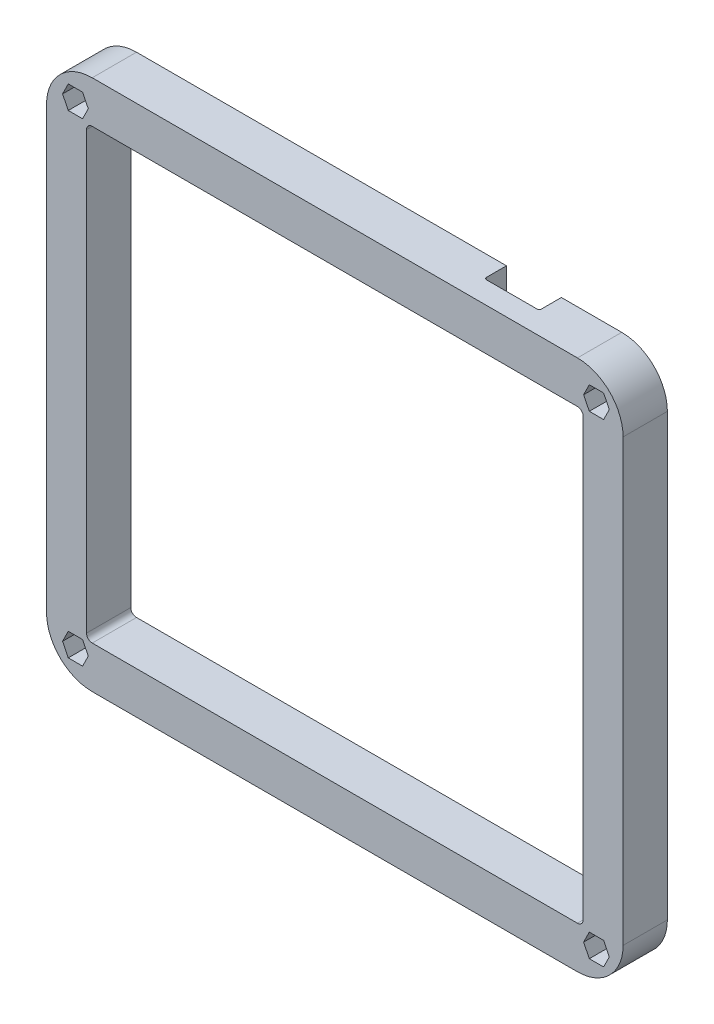
SolidWorks part; units mm, degrees
ref_plane "Ebene vorne" through (0, 0, 0) normal (0, 0, 1) x (1, 0, 0)
ref_plane "Ebene oben" through (0, 0, 0) normal (0, 1, 0) x (1, 0, 0)
ref_plane "Ebene rechts" through (0, 0, 0) normal (1, 0, 0) x (0, 0, -1)
sketch "Skizze1" plane through (0, 0, 0) normal (0, 0, 1) x (1, 0, 0)
  line L0 (-169.0581, -51.0905) -> (-85.55, -51.0905) construction
  line L1 (-169.0581, -41.5905) -> (-85.55, -41.5905) construction
  line L2 (-59.5275, -41.5905) -> (-73.15, -41.5905) construction
  line L3 (-59.5275, -51.0905) -> (-73.15, -51.0905) construction
  line L4 (-179.3474, -150.8036) -> (-179.3474, -52.3842) construction
  line L10 (-73.15, -41.5905) -> (-85.55, -41.5905)
  line L11 (-170.3518, -150.803) -> (-170.3518, -52.3842) construction
  line L12 (-58.2338, -52.3842) -> (-58.2338, -150.803) construction
  line L14 (-59.5275, -161.5967) -> (-169.0581, -161.5967) construction
  line L15 (-59.5275, -152.0967) -> (-169.0581, -152.0967) construction
  line L21 (-73.15, -51.0905) -> (-85.55, -51.0905)
  line L22 (-176.1768, -155.0967) -> (-167.1691, -155.0967) construction
  line L23 (-172.8474, -149.9491) -> (-172.8474, -160.7097) construction
  line L30 (-56.8493, -152.4967) -> (-53.6183, -152.4967)
  line L31 (-53.6183, -152.4967) -> (-52.3338, -155.0967)
  line L32 (-52.3338, -155.0967) -> (-53.6183, -157.6967)
  line L33 (-53.6183, -157.6967) -> (-56.8493, -157.6967)
  line L34 (-56.8493, -157.6967) -> (-58.1338, -155.0967)
  line L35 (-58.1338, -155.0967) -> (-56.8493, -152.4967)
  line L36 (-55.2338, -149.418) -> (-55.2338, -157.4313) construction
  line L37 (-53.5053, -155.0967) -> (-60.8819, -155.0967) construction
  line L38 (-55.2338, -45.3904) -> (-55.2338, -52.2981) construction
  line L39 (-59.8357, -48.0905) -> (-52.3338, -48.0905) construction
  line L40 (-56.8493, -45.4905) -> (-53.6183, -45.4905)
  line L41 (-53.6183, -45.4905) -> (-52.3338, -48.0905)
  line L42 (-52.3338, -48.0905) -> (-53.6183, -50.6905)
  line L43 (-53.6183, -50.6905) -> (-56.8493, -50.6905)
  line L44 (-56.8493, -50.6905) -> (-58.1338, -48.0905)
  line L45 (-58.1338, -48.0905) -> (-56.8493, -45.4905)
  line L46 (-172.8474, -46.2241) -> (-172.8474, -53.8481) construction
  line L47 (-169.0581, -51.0905) -> (-85.55, -51.0905)
  line L48 (-174.4629, -45.4905) -> (-171.2319, -45.4905)
  line L49 (-171.2319, -45.4905) -> (-169.9474, -48.0905)
  line L50 (-169.9474, -48.0905) -> (-171.2319, -50.6905)
  line L51 (-171.2319, -50.6905) -> (-174.4629, -50.6905)
  line L52 (-174.4629, -50.6905) -> (-175.7474, -48.0905)
  line L53 (-175.7474, -48.0905) -> (-174.4629, -45.4905)
  line L60 (-171.2319, -152.4967) -> (-174.4629, -152.4967)
  line L61 (-174.4629, -152.4967) -> (-175.7474, -155.0967)
  line L62 (-175.7474, -155.0967) -> (-174.4629, -157.6967)
  line L63 (-174.4629, -157.6967) -> (-171.2319, -157.6967)
  line L64 (-171.2319, -157.6967) -> (-169.9474, -155.0967)
  line L65 (-169.9474, -155.0967) -> (-171.2319, -152.4967)
  line L66 (-167.3158, -48.0905) -> (-176.3704, -48.0905) construction
  line L67 (-49.2275, -51.8905) -> (-49.2275, -151.2967) construction
  line L68 (-49.2275, -51.8905) -> (-49.2275, -151.2967)
  line L83 (-169.0581, -41.5905) -> (-85.55, -41.5905)
  line L84 (-59.5275, -41.5905) -> (-73.15, -41.5905)
  line L85 (-59.5275, -51.0905) -> (-73.15, -51.0905)
  line L86 (-179.3474, -150.8036) -> (-179.3474, -52.3842)
  line L87 (-170.3518, -150.803) -> (-170.3518, -52.3842)
  line L88 (-58.2338, -52.3842) -> (-58.2338, -150.803)
  line L90 (-59.5275, -161.5967) -> (-169.0581, -161.5967)
  line L91 (-59.5275, -152.0967) -> (-169.0581, -152.0967)
  arc A0 (-169.0581, -51.0905) -> (-170.3518, -52.3842) centre (-169.0581, -52.3842) ccw construction
  arc A1 (-169.0581, -41.5905) -> (-179.3474, -52.3842) centre (-169.0581, -51.8916) ccw construction
  arc A2 (-58.2338, -52.3842) -> (-59.5275, -51.0905) centre (-59.5275, -52.3842) ccw construction
  arc A8 (-179.3474, -150.8036) -> (-169.0581, -161.5967) centre (-169.0581, -151.2956) ccw construction
  arc A9 (-170.3518, -150.803) -> (-169.0581, -152.0967) centre (-169.0581, -150.803) ccw construction
  arc A10 (-59.5275, -152.0967) -> (-58.2338, -150.803) centre (-59.5275, -150.803) ccw construction
  arc A16 (-49.2275, -51.8905) -> (-59.5275, -41.5905) centre (-59.5275, -51.8905) ccw construction
  arc A17 (-59.5275, -161.5967) -> (-49.2275, -151.2967) centre (-59.5275, -151.2967) ccw construction
  arc A18 (-49.2275, -51.8905) -> (-59.5275, -41.5905) centre (-59.5275, -51.8905) ccw
  arc A19 (-59.5275, -161.5967) -> (-49.2275, -151.2967) centre (-59.5275, -151.2967) ccw
  arc A32 (-169.0581, -51.0905) -> (-170.3518, -52.3842) centre (-169.0581, -52.3842) ccw
  arc A33 (-169.0581, -41.5905) -> (-179.3474, -52.3842) centre (-169.0581, -51.8916) ccw
  arc A34 (-58.2338, -52.3842) -> (-59.5275, -51.0905) centre (-59.5275, -52.3842) ccw
  arc A36 (-179.3474, -150.8036) -> (-169.0581, -161.5967) centre (-169.0581, -151.2956) ccw
  arc A37 (-170.3518, -150.803) -> (-169.0581, -152.0967) centre (-169.0581, -150.803) ccw
  arc A38 (-59.5275, -152.0967) -> (-58.2338, -150.803) centre (-59.5275, -150.803) ccw
  point P80 (-170.5897, -49.3905)
  dimension "D2" = 5.2
  dimension "D3" = 5.2
  dimension "D4" = 5.8
  dimension "D5" = 5.2
  dimension "D6" = 5.2
  dimension "D7" = 5.2
  dimension "D8" = 5.8
  dimension "D9" = 5.2
  dimension "D10" = 5.2
  dimension "D11" = 5.2
  dimension "D12" = 5.8
  dimension "D13" = 5.2
  dimension "D14" = 5.2
  dimension "D15" = 5.2
  dimension "D16" = 5.8
extrude "Aufsatz-Linear austragen1" add sketch "Skizze1" along normal blind 10
sketch "Skizze2" plane through (0, -41.5905, 0) normal (0, 1, 0) x (1, 0, 0)
  line L2 (-85.55, 0) -> (-85.55, -5)
  line L4 (-73.15, 0) -> (-73.15, -5)
  line L5 (-73.15, -5) -> (-85.55, -5)
  line L7 (-73.15, 0) -> (-85.55, 0)
  dimension "D1" = 5
extrude "Schnitt-Linear austragen1" cut sketch "Skizze2" against normal up to next
fillet "Verrundung1" radius 0.5 2 edges at (-73.15, -46.3405, 5) (-85.55, -46.3405, 5)
